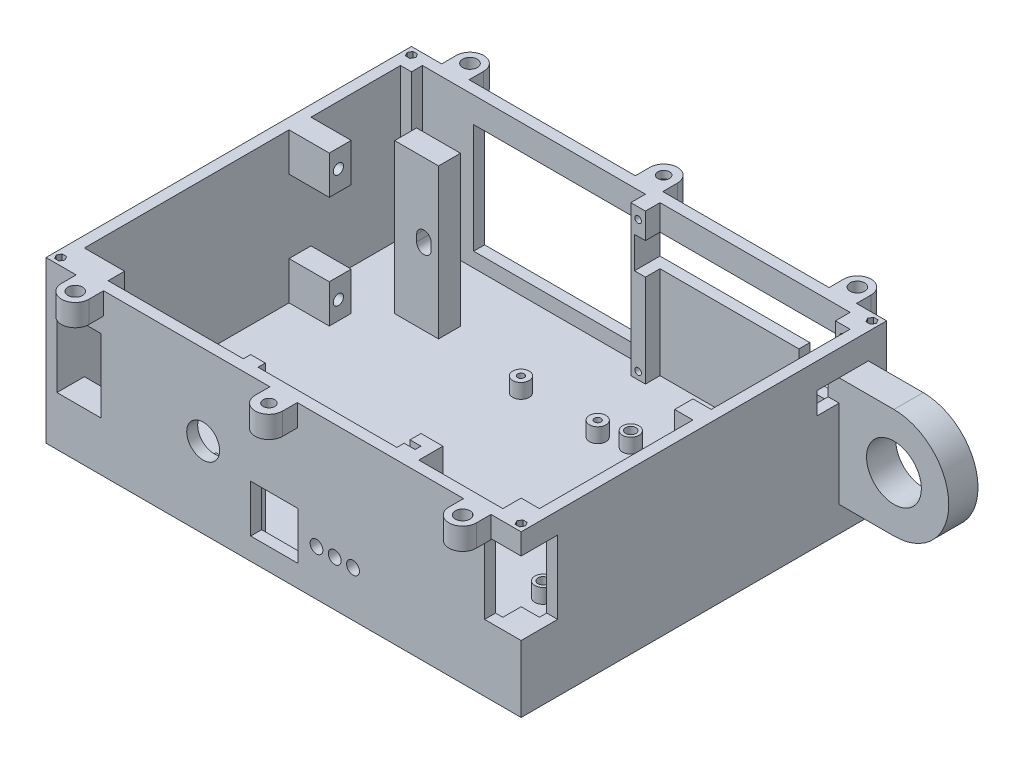
SolidWorks part; units mm, degrees
ref_plane "Front Plane" through (0, 0, 0) normal (0, 0, 1) x (1, 0, 0)
ref_plane "Top Plane" through (0, 0, 0) normal (0, 1, 0) x (1, 0, 0)
ref_plane "Right Plane" through (0, 0, 0) normal (1, 0, 0) x (0, 0, -1)
sketch "Sketch1" plane through (0, 0, 0) normal (0, 1, 0) x (1, 0, 0)
  line L1 (0, 0) -> (130, 0)
  line L2 (0, 0) -> (0, -100)
  line L3 (0, -100) -> (130, -100)
  line L4 (130, 0) -> (130, -100)
  dimension "D1" = 100
  dimension "D2" = 130
extrude "Boss-Extrude1" add sketch "Sketch1" along normal blind 44
sketch "Sketch3" plane through (0, 44, 0) normal (0, 1, 0) x (1, 0, 0)
  line L0 (0, 0) -> (0, -100) construction
  line L1 (14, -3) -> (67, -3)
  line L2 (3, -36.5) -> (3, -92.5)
  line L5 (127, -45) -> (127, -7)
  line L6 (122, -45) -> (127, -45)
  line L7 (130, 0) -> (0, 0) construction
  line L8 (3, -3) -> (14, -3) construction
  line L9 (14, -3) -> (14, -32) construction
  line L10 (14, -34) -> (14, -95) construction
  line L11 (14, -95) -> (14, -97) construction
  line L12 (14, -97) -> (122, -97)
  line L13 (14, -36.5) -> (3, -36.5)
  line L17 (14, -92.5) -> (3, -92.5)
  line L30 (127, -92) -> (127, -50)
  line L31 (130, -100) -> (130, 0) construction
  line L32 (0, -100) -> (130, -100) construction
  line L33 (122, -97) -> (122, -92.75) construction
  line L34 (122, -92.75) -> (122, -49.25) construction
  line L35 (122, -49.25) -> (122, -45) construction
  line L36 (122, -45) -> (122, -50)
  line L37 (122, -50) -> (127, -50)
  line L40 (122, -97) -> (122, -92)
  line L41 (122, -92) -> (127, -92)
  line L42 (14, -32) -> (14, -34) construction
  line L44 (14, -92.5) -> (14, -97)
  line L45 (127, -7) -> (125, -7) construction
  line L46 (125, -7) -> (69, -7) construction
  line L47 (69, -7) -> (67, -7) construction
  line L48 (71, -3) -> (123, -3)
  line L49 (67, -7) -> (71, -7)
  line L50 (67, -7) -> (67, -3)
  line L52 (71, -7) -> (71, -3)
  line L53 (127, -7) -> (123, -7)
  line L56 (123, -7) -> (123, -3)
  line L57 (14, -36.5) -> (14, -30.5)
  line L58 (14, -30.5) -> (3, -30.5)
  line L59 (3, -30.5) -> (3, -6)
  line L60 (14, -3) -> (6, -3)
  line L64 (3, -6) -> (6, -6)
  line L65 (6, -3) -> (6, -6)
  dimension "D1" = 3
  dimension "D2" = 3
  dimension "D3" = 3
  dimension "D4" = 3
  dimension "D5" = 65
  dimension "D6" = 61
  dimension "D7" = 2.5
  dimension "D8" = 2.5
  dimension "D9" = 43.5
  dimension "D10" = 5
  dimension "D11" = 6
  dimension "D12" = 5
  dimension "52" = 52
  dimension "D13" = 5
  dimension "D14" = 11
  dimension "D15" = 60
  dimension "D16" = 4
  dimension "D17" = 2
  dimension "D18" = 4
  dimension "D19" = 3
extrude "Cut-Extrude1" cut sketch "Sketch3" against normal blind 41
sketch "Sketch4" plane through (0, 0, 100) normal (0, 0, 1) x (1, 0, 0)
  line L0 (3, 44) -> (3, 33.5) construction
  line L1 (0, 44) -> (130, 44) construction
  line L2 (3, 33.5) -> (3, 13.5) construction
  line L3 (3, 13.5) -> (3, 3) construction
  line L5 (0, 44) -> (0, 0) construction
  line L6 (3, 3) -> (3, 0) construction
  line L7 (3, 33.5) -> (15, 33.5)
  line L8 (3, 33.5) -> (3, 13.5)
  line L9 (3, 13.5) -> (15, 13.5)
  line L10 (15, 33.5) -> (15, 13.5)
  line L11 (0, 0) -> (130, 0) construction
  dimension "D2" = 3
  dimension "D3" = 3
  dimension "D4" = 12
  dimension "D5" = 20
extrude "Cut-Extrude2" cut sketch "Sketch4" against normal up to surface (69.5 mm away) up to face at (8.5, 23.5, 30.5)
sketch "Sketch11" plane through (14, 0, 0) normal (1, 0, 0) x (0, 0, -1)
  line L0 (-95, 44) -> (-95, 39) construction
  line L1 (-100, 44) -> (0, 44) construction
  line L2 (-95, 39) -> (-95, 8) construction
  line L3 (-95, 8) -> (-95, 3) construction
  line L4 (-95, 3) -> (-95, 0) construction
  line L5 (-100, 0) -> (0, 0) construction
  line L6 (-100, 39) -> (-97, 39) construction
  line L7 (-100, 44) -> (-100, 0) construction
  line L8 (-97, 39) -> (-95, 39) construction
  line L9 (-95, 39) -> (-34, 39) construction
  line L10 (-34, 39) -> (-32, 39) construction
  line L11 (-32, 39) -> (0, 39) construction
  line L12 (0, 44) -> (0, 0) construction
  line L13 (-95, 8) -> (-34, 8) construction
  circle A0 centre (-95, 39) radius 1.4
  circle A1 centre (-95, 8) radius 1.4
  circle A2 centre (-34, 39) radius 1.4
  circle A3 centre (-34, 8) radius 1.4
  dimension "D6" = 2.8
  dimension "D1" = 3
  dimension "D2" = 31
  dimension "D3" = 3
  dimension "D4" = 65
  dimension "D5" = 61
extrude "Cut-Extrude6" cut sketch "Sketch11" against normal up to surface (11 mm away) up to face at (3, 23.5, 53.125)
sketch "Sketch12" plane through (0, 0, 0) normal (0, 0, -1) x (-1, 0, 0)
  line L0 (0, 37) -> (-3, 37) construction
  line L1 (0, 44) -> (0, 0) construction
  line L2 (-3, 37) -> (-17, 37) construction
  line L3 (-20, 37) -> (-66, 37) construction
  line L4 (-66, 37) -> (-66, 7) construction
  line L5 (-66, 37) -> (-66, 44) construction
  line L6 (-130, 44) -> (0, 44) construction
  line L7 (-66, 7) -> (-66, 0) construction
  line L8 (-130, 0) -> (0, 0) construction
  line L9 (-17, 37) -> (-20, 37) construction
  line L10 (-66, 37) -> (-20, 37)
  line L11 (-66, 37) -> (-66, 7)
  line L12 (-66, 7) -> (-20, 7)
  line L13 (-20, 37) -> (-20, 7)
  dimension "D1" = 3
  dimension "D2" = 3
  dimension "D3" = 46
  dimension "D4" = 30
  dimension "D5" = 14
extrude "Cut-Extrude7" cut sketch "Sketch12" against normal up to surface (3 mm away) up to face at (36.5, 23.5, 3)
sketch "Sketch14" plane through (0, 0, 97) normal (0, 0, -1) x (-1, 0, 0)
  line L0 (-66, 22) -> (-43, 22) construction
  line L1 (-66, 37) -> (-66, 7) construction
  line L2 (-43, 22) -> (-43, 7) construction
  line L3 (-66, 7) -> (-20, 7) construction
  circle A0 centre (-43, 22) radius 4.5
  dimension "D3" = 9
  dimension "D1" = 23
  dimension "D2" = 15
extrude "Cut-Extrude8" cut sketch "Sketch14" against normal up to surface (3 mm away) up to face at (9, 23.5, 100)
sketch "Sketch15" plane through (0, 0, 97) normal (0, 0, -1) x (-1, 0, 0)
  line L0 (-43, 22) -> (-43, 31.5) construction
  line L1 (-43, 22) -> (-43, 12.5) construction
  line L3 (-45.5, 29) -> (-40.5, 29)
  line L4 (-45.5, 29) -> (-45.5, 34)
  line L5 (-45.5, 34) -> (-40.5, 34)
  line L6 (-40.5, 29) -> (-40.5, 34)
  line L7 (-40.5, 15) -> (-45.5, 15)
  line L8 (-40.5, 15) -> (-40.5, 10)
  line L9 (-40.5, 10) -> (-45.5, 10)
  line L10 (-45.5, 15) -> (-45.5, 10)
  circle A0 centre (-43, 31.5) radius 1.4
  circle A1 centre (-43, 12.5) radius 1.4
  dimension "D7" = 2.8
  dimension "D1" = 9.5
  dimension "D2" = 2.5
  dimension "D3" = 2.5
  dimension "D4" = 5
  dimension "D5" = 2.5
  dimension "D6" = 2.5
extrude "Boss-Extrude2" add sketch "Sketch15" along normal blind 3
sketch "Sketch20" plane through (0, 44, 0) normal (0, 1, 0) x (1, 0, 0)
  line L0 (130, -97) -> (96, -97) construction
  line L1 (130, -100) -> (130, 0) construction
  line L2 (96, -97) -> (51, -97) construction
  line L3 (51, -97) -> (43, -97) construction
  line L4 (0, -100) -> (130, -100) construction
  line L5 (93, -97) -> (99, -97)
  line L6 (99, -97) -> (99, -90.4)
  line L7 (99, -90.4) -> (93, -90.4)
  line L8 (93, -90.4) -> (93, -93.4)
  line L9 (93, -93.4) -> (96, -93.4)
  line L10 (96, -93.4) -> (96, -95)
  line L11 (96, -95) -> (93, -95)
  line L12 (93, -95) -> (93, -97)
  line L14 (51, -97) -> (55, -97)
  line L15 (51, -97) -> (51, -95)
  line L16 (51, -95) -> (55, -95)
  line L17 (55, -97) -> (55, -95)
  dimension "D1" = 87
  dimension "D2" = 8
  dimension "D3" = 3
  dimension "40" = 45
  dimension "D5" = 3
  dimension "D6" = 3
  dimension "D7" = 1.6
  dimension "D8" = 2
  dimension "D9" = 3
  dimension "D10" = 3
  dimension "D11" = 2
  dimension "D12" = 4
extrude "Boss-Extrude3" add sketch "Sketch20" against normal up to surface (41 mm away) up to face at (66.5833, 3, 39.125)
sketch "Sketch21" plane through (130, 0, 0) normal (1, 0, 0) x (0, 0, -1)
  line L0 (0, 22) -> (-5, 22) construction
  line L1 (0, 44) -> (0, 0) construction
  line L2 (-5, 22) -> (-5, 37) construction
  line L4 (-5, 37) -> (-13, 37)
  line L5 (-5, 37) -> (-5, 7)
  line L6 (-5, 7) -> (-13, 7)
  line L7 (-13, 37) -> (-13, 7)
  dimension "D1" = 5
  dimension "D2" = 15
  dimension "D3" = 8
  dimension "D4" = 30
extrude "Boss-Extrude4" add sketch "Sketch21" along normal blind 30
sketch "Sketch23" plane through (0, 0, 5) normal (0, 0, -1) x (-1, 0, 0)
  line L0 (-160, 37) -> (-130, 7) construction
  line L2 (-145, 37) -> (-169.0246, 37)
  line L4 (-145, 7) -> (-169.0246, 7)
  line L5 (-169.0246, 37) -> (-169.0246, 7)
  circle A0 centre (-145, 22) radius 7.5
  arc A1 (-145, 37) -> (-145, 7) centre (-145, 22) ccw
  dimension "D1" = 15
  dimension "D2" = 15
extrude "Cut-Extrude9" cut sketch "Sketch23" against normal up to surface (8 mm away) up to face at (145, 22, 13)
sketch "Sketch24" plane through (130, 0, 0) normal (1, 0, 0) x (0, 0, -1)
  line L1 (-13, 37) -> (-19, 37)
  line L2 (-13, 37) -> (-13, 31)
  line L3 (-13, 31) -> (-19, 31)
  line L4 (-19, 37) -> (-19, 31)
  dimension "D1" = 6
extrude "Cut-Extrude10" cut sketch "Sketch24" against normal up to surface (3 mm away) up to face at (127, 23.5, 26)
sketch "Sketch25" plane through (0, 0, 95) normal (0, 0, -1) x (-1, 0, 0)
  line L0 (-53, 44) -> (-53, 41.65) construction
  line L1 (-130, 44) -> (0, 44) construction
  line L2 (-53, 41.65) -> (-53, 5.35) construction
  line L3 (-53, 5.35) -> (-53, 3) construction
  line L4 (-53, 3) -> (-53, 0) construction
  line L5 (-130, 0) -> (0, 0) construction
  line L6 (-55, 3) -> (-55, 44) construction
  circle A0 centre (-53, 41.65) radius 1
  circle A1 centre (-53, 5.35) radius 1
  dimension "D4" = 2
  dimension "D1" = 3
  dimension "D2" = 36.3
  dimension "D3" = 2
extrude "Cut-Extrude11" cut sketch "Sketch25" against normal blind 3
sketch "Sketch26" plane through (0, 3, 0) normal (0, 1, 0) x (1, 0, 0)
  line L0 (51, -97) -> (51, -80) construction
  line L1 (51, -15.6) -> (51, -26.05) construction
  line L2 (51, -15.6) -> (51, 0) construction
  line L3 (130, 0) -> (0, 0) construction
  line L4 (51, -26.05) -> (51, -69.55) construction
  line L5 (51, -69.55) -> (51, -80) construction
  line L6 (51, -26.05) -> (56, -26.05) construction
  line L8 (56, -26.05) -> (77, -26.05) construction
  line L9 (56, -26.05) -> (56, -69.55) construction
  line L10 (56, -69.55) -> (77, -69.55) construction
  line L11 (77, -26.05) -> (77, -69.55) construction
  circle A0 centre (56, -26.05) radius 2.25
  circle A1 centre (77, -26.05) radius 0.9
  circle A2 centre (56, -69.55) radius 2.25
  circle A3 centre (77, -69.55) radius 0.9
  circle A4 centre (56, -26.05) radius 0.9
  circle A5 centre (77, -26.05) radius 2.25
  circle A6 centre (56, -69.55) radius 0.9
  circle A7 centre (77, -69.55) radius 2.25
  dimension "D6" = 1.8
  dimension "D7" = 4.5
  dimension "D1" = 15.6
  dimension "D2" = 17
  dimension "D3" = 43.5
  dimension "D4" = 5
  dimension "D5" = 21
extrude "Boss-Extrude5" add sketch "Sketch26" along normal blind 4
sketch "Sketch27" plane through (122, 0, 0) normal (-1, 0, 0) x (0, 0, 1)
  line L0 (100, 40) -> (97, 40) construction
  line L1 (100, 44) -> (100, 0) construction
  line L2 (97, 40) -> (94.25, 40) construction
  line L3 (94.25, 40) -> (47.75, 40) construction
  line L4 (47.75, 40) -> (45, 40) construction
  line L5 (47.75, 40) -> (47.75, 16.5) construction
  line L6 (47.75, 16.5) -> (47.75, 3) construction
  line L7 (47.75, 3) -> (47.75, 0) construction
  line L8 (0, 0) -> (100, 0) construction
  line L9 (47.75, 40) -> (47.75, 44) construction
  line L10 (0, 44) -> (100, 44) construction
  line L11 (47.75, 16.5) -> (94.25, 16.5) construction
  circle A0 centre (47.75, 40) radius 0.9
  circle A1 centre (47.75, 16.5) radius 0.9
  circle A2 centre (94.25, 40) radius 0.9
  circle A3 centre (94.25, 16.5) radius 0.9
  dimension "D6" = 1.8
  dimension "D1" = 3
  dimension "D2" = 46.5
  dimension "D3" = 52
  dimension "D4" = 3
  dimension "D5" = 23.5
  dimension "D7" = 4
extrude "Cut-Extrude12" cut sketch "Sketch27" against normal up to surface (5 mm away) up to face at (127, 23.5, 71)
sketch "Sketch28" plane through (0, 0, 100) normal (0, 0, 1) x (1, 0, 0)
  line L0 (122, 0) -> (122, 3) construction
  line L1 (0, 0) -> (130, 0) construction
  line L2 (122, 38.25) -> (122, 40) construction
  line L3 (122, 18.25) -> (122, 38.25) construction
  line L4 (122, 40) -> (122, 44) construction
  line L7 (126, 38.25) -> (120, 38.25)
  line L8 (126, 38.25) -> (126, 18.25)
  line L9 (126, 18.25) -> (120, 18.25)
  line L10 (120, 38.25) -> (120, 18.25)
  line L11 (0, 44) -> (130, 44) construction
  line L12 (122, 18.25) -> (122, 16.5) construction
  line L13 (122, 16.5) -> (122, 3) construction
  dimension "D1" = 3
  dimension "D2" = 20
  dimension "D3" = 4
  dimension "D4" = 6
  dimension "D5" = 4
  dimension "D6" = 23.5
extrude "Cut-Extrude13" cut sketch "Sketch28" against normal up to surface (55 mm away) up to face at (124.5, 23.5, 45)
sketch "Sketch29" plane through (0, 0, 0) normal (0, 0, -1) x (-1, 0, 0)
  line L0 (-130, 37) -> (-123, 37) construction
  line L1 (-130, 44) -> (-130, 0) construction
  line L2 (-130, 44) -> (0, 44) construction
  line L3 (-123, 37) -> (-123, 20)
  line L4 (-123, 20) -> (-109, 20)
  line L5 (-109, 20) -> (-109, 28.3447)
  line L6 (-109, 28.3447) -> (-68, 28.3447)
  line L7 (-68, 28.3447) -> (-68, 37)
  line L8 (-68, 37) -> (-123, 37)
  dimension "D1" = 7
  dimension "D2" = 7
  dimension "D3" = 17
  dimension "D4" = 14
  dimension "D5" = 55
extrude "Cut-Extrude14" cut sketch "Sketch29" against normal up to surface (7 mm away) up to face at (69, 23.5, 7)
sketch "Sketch30" plane through (0, 0, 7) normal (0, 0, 1) x (1, 0, 0)
  line L0 (130, 41) -> (127, 41) construction
  line L1 (130, 44) -> (130, 0) construction
  line L2 (127, 41) -> (125, 41) construction
  line L3 (0, 44) -> (130, 44) construction
  line L5 (125, 41) -> (69, 41) construction
  line L6 (125, 41) -> (125, 5) construction
  line L7 (125, 5) -> (69, 5) construction
  line L8 (69, 41) -> (69, 5) construction
  circle A0 centre (69, 41) radius 0.9
  circle A1 centre (69, 5) radius 0.9
  circle A2 centre (125, 5) radius 0.9
  circle A3 centre (125, 41) radius 0.9
  dimension "D6" = 1.8
  dimension "D1" = 3
  dimension "D2" = 2
  dimension "D3" = 3
  dimension "D4" = 56
  dimension "D5" = 36
extrude "Cut-Extrude15" cut sketch "Sketch30" against normal up to surface (4 mm away) up to face at (101, 17.1149, 3)
sketch "Sketch31" plane through (0, 0, 97) normal (0, 0, -1) x (-1, 0, 0)
  line L0 (-55, 3) -> (-56, 3) construction
  line L1 (-55, 3) -> (-55, 44) construction
  line L2 (-56, 3) -> (-56, 6) construction
  line L3 (-130, 0) -> (0, 0) construction
  line L4 (-56, 6) -> (-69, 6)
  line L5 (-69, 6) -> (-69, 19)
  line L8 (-69, 19) -> (-56, 19)
  line L9 (-56, 19) -> (-56, 6)
  line L10 (-69, 12.5) -> (-74, 12.5) construction
  line L11 (-74, 12.5) -> (-79, 12.5) construction
  line L12 (-79, 12.5) -> (-84, 12.5) construction
  circle A0 centre (-74, 12.5) radius 1.75
  circle A1 centre (-79, 12.5) radius 1.75
  circle A2 centre (-84, 12.5) radius 1.75
  dimension "D7" = 3.5
  dimension "D1" = 3
  dimension "D2" = 1
  dimension "D3" = 3
  dimension "D4" = 13
  dimension "D5" = 13
  dimension "D6" = 5
extrude "Cut-Extrude16" cut sketch "Sketch31" against normal up to surface (3 mm away) up to face at (123, 28.25, 100)
sketch "Sketch34" plane through (0, 3, 0) normal (0, 1, 0) x (1, 0, 0)
  line L0 (3, -18.6) -> (20, -18.6) construction
  line L1 (3, -6) -> (3, -30.5) construction
  line L2 (67, -3) -> (6, -3) construction
  line L4 (20, -18.6) -> (32, -18.6)
  line L5 (20, -18.6) -> (20, -24.6)
  line L6 (20, -24.6) -> (32, -24.6)
  line L7 (32, -18.6) -> (32, -24.6)
  dimension "D1" = 17
  dimension "D2" = 15.6
  dimension "D3" = 12
  dimension "D4" = 6
extrude "Boss-Extrude6" add sketch "Sketch34" along normal up to surface (41 mm away) up to face at (71.4444, 44, 57.6278)
sketch "Sketch35" plane through (0, 0, 18.6) normal (0, 0, -1) x (-1, 0, 0)
  line L0 (-20, 23) -> (-28, 23) construction
  line L1 (-20, 7) -> (-20, 37) construction
  line L2 (-20, 37) -> (-66, 37) construction
  line L3 (-20, 24.8) -> (-28, 24.8) construction
  line L6 (-30, 24.8) -> (-30, 23)
  line L8 (-26, 24.8) -> (-26, 23)
  arc A0 (-30, 23) -> (-26, 23) centre (-28, 23) ccw
  arc A2 (-26, 24.8) -> (-30, 24.8) centre (-28, 24.8) ccw
  dimension "D3" = 4
  dimension "D1" = 8
  dimension "D2" = 14
  dimension "D4" = 12.2
extrude "Cut-Extrude17" cut sketch "Sketch35" against normal up to surface (6 mm away) up to face at (26, 23.5, 24.6)
sketch "Sketch36" plane through (0, 44, 0) normal (0, 1, 0) x (1, 0, 0)
  line L0 (0, 0) -> (12, 0) construction
  line L1 (65, 0) -> (12, 0) construction
  line L2 (130, 0) -> (0, 0) construction
  line L3 (65, 0) -> (118, 0) construction
  line L4 (118, 0) -> (130, 0) construction
  line L5 (0, 0) -> (0, -100) construction
  line L6 (0, -100) -> (130, -100) construction
  line L7 (65, 0) -> (65, -100) construction
  line L8 (118, 0) -> (118, -100) construction
  line L10 (12, 4) -> (118, 4) construction
  line L11 (118, 4) -> (118, 0) construction
  line L12 (65, 0) -> (65, 4) construction
  line L13 (12, -100) -> (12, -104) construction
  line L14 (12, -104) -> (118, -104) construction
  line L15 (118, -104) -> (118, -100) construction
  line L16 (65, -100) -> (65, -104) construction
  line L19 (8.25, 4) -> (8.25, 0)
  line L20 (8.25, 0) -> (15.75, 0)
  line L21 (15.75, 4) -> (15.75, 0)
  line L23 (61.25, 4) -> (61.25, 0)
  line L24 (61.25, 0) -> (68.75, 0)
  line L25 (68.75, 4) -> (68.75, 0)
  line L27 (114.25, 4) -> (114.25, 0)
  line L28 (114.25, 0) -> (121.75, 0)
  line L29 (121.75, 4) -> (121.75, 0)
  line L31 (8.25, -104) -> (8.25, -100)
  line L32 (8.25, -100) -> (15.75, -100)
  line L33 (15.75, -104) -> (15.75, -100)
  line L35 (61.25, -104) -> (61.25, -100)
  line L36 (61.25, -100) -> (68.75, -100)
  line L37 (68.75, -104) -> (68.75, -100)
  line L39 (121.75, -104) -> (121.75, -100)
  line L40 (121.75, -100) -> (114.25, -100)
  line L41 (114.25, -104) -> (114.25, -100)
  arc A0 (15.75, 4) -> (8.25, 4) centre (12, 4) ccw
  circle A1 centre (12, 4) radius 2
  arc A2 (68.75, 4) -> (61.25, 4) centre (65, 4) ccw
  circle A3 centre (65, 4) radius 1.6
  arc A4 (121.75, 4) -> (114.25, 4) centre (118, 4) ccw
  circle A5 centre (118, 4) radius 2
  arc A6 (8.25, -104) -> (15.75, -104) centre (12, -104) ccw
  circle A7 centre (12, -104) radius 2
  arc A8 (61.25, -104) -> (68.75, -104) centre (65, -104) ccw
  circle A9 centre (65, -104) radius 1.6
  arc A10 (114.25, -104) -> (121.75, -104) centre (118, -104) ccw
  circle A11 centre (118, -104) radius 2
  dimension "D1" = 4
  dimension "D2" = 7.5
  dimension "D4" = 3.2
  dimension "D3" = 4
  dimension "D5" = 12
  dimension "D6" = 4
extrude "Boss-Extrude7" add sketch "Sketch36" against normal blind 6
sketch "Sketch37" plane through (0, 38, 0) normal (0, -1, 0) x (1, 0, 0)
  circle A0 centre (65, 104) radius 2
  circle A1 centre (65, -4) radius 2
  dimension "D1" = 4
extrude "Cut-Extrude18" cut sketch "Sketch37" against normal blind 4 contours A1
sketch "Sketch38" plane through (0, 3, 0) normal (0, 1, 0) x (1, 0, 0)
  line L0 (84, -47.8) -> (77, -47.8) construction
  line L1 (84, -24) -> (107.6, -24) construction
  line L2 (84, -24) -> (84, -71.6) construction
  line L3 (84, -71.6) -> (107.6, -71.6) construction
  line L4 (107.6, -24) -> (107.6, -71.6) construction
  line L5 (77, -47.8) -> (77, -26.05) construction
  line L6 (77, -47.8) -> (77, -69.55) construction
  circle A0 centre (84, -24) radius 1.4
  circle A1 centre (84, -24) radius 2.25
  circle A2 centre (107.6, -24) radius 1.4
  circle A3 centre (107.6, -24) radius 2.25
  circle A4 centre (84, -71.6) radius 2.25
  circle A5 centre (84, -71.6) radius 1.4
  circle A6 centre (107.6, -71.6) radius 2.25
  circle A7 centre (107.6, -71.6) radius 1.4
  dimension "D3" = 2.8
  dimension "D4" = 4.5
  dimension "D1" = 47.6
  dimension "D2" = 23.6
  dimension "D5" = 7
extrude "Boss-Extrude8" add sketch "Sketch38" along normal blind 4
sketch "Sketch40" plane through (0, 0, 45) normal (0, 0, -1) x (-1, 0, 0)
  line L0 (-127, 44) -> (-127, 40) construction
  line L1 (-130, 44) -> (-121.75, 44) construction
  line L2 (-127, 40) -> (-127, 38.25) construction
  line L3 (-127, 38.25) -> (-127, 18.25) construction
  line L5 (-127, 18.25) -> (-127, 16.5) construction
  line L6 (-127, 16.5) -> (-127, 0) construction
  line L7 (-130, 0) -> (0, 0) construction
  line L8 (-130, 44) -> (-130, 0) construction
  line L10 (-127, 38.25) -> (-122, 38.25)
  line L11 (-127, 38.25) -> (-127, 18.25)
  line L12 (-127, 18.25) -> (-122, 18.25)
  line L13 (-122, 38.25) -> (-122, 18.25)
  dimension "D1" = 4
  dimension "D2" = 23.5
  dimension "D3" = 20
  dimension "D4" = 3
  dimension "D5" = 5
extrude "Cut-Extrude20" cut sketch "Sketch40" against normal up to surface (52 mm away) up to face at (115.75, 25.875, 97)
sketch "Sketch41" plane through (0, 0, 100) normal (0, 0, 1) x (1, 0, 0)
  line L0 (130, 31) -> (130, 7) construction
  line L1 (126, 38.25) -> (130, 38.25)
  line L2 (126, 38.25) -> (126, 18.25)
  line L3 (126, 18.25) -> (130, 18.25)
  line L4 (130, 38.25) -> (130, 18.25)
  dimension "D1" = 20
extrude "Cut-Extrude21" cut sketch "Sketch41" against normal blind 10
sketch "Sketch42" plane through (0, 44, 0) normal (0, 1, 0) x (1, 0, 0)
  line L0 (130, -100) -> (130, 0) construction
  line L1 (2, -2) -> (128, -2) construction
  line L2 (2, -2) -> (2, -98) construction
  line L3 (2, -98) -> (128, -98) construction
  line L4 (128, -2) -> (128, -98) construction
  line L5 (121.75, -100) -> (130, -100) construction
  line L6 (0, 0) -> (0, -100) construction
  line L7 (61.25, 0) -> (15.75, 0) construction
  line L9 (3.2124, -2) -> (2.6062, -0.95)
  line L10 (2.6062, -0.95) -> (1.3938, -0.95)
  line L11 (1.3938, -0.95) -> (0.7876, -2)
  line L12 (0.7876, -2) -> (1.3938, -3.05)
  line L13 (1.3938, -3.05) -> (2.6062, -3.05)
  line L14 (2.6062, -3.05) -> (3.2124, -2)
  line L15 (126.7876, -2) -> (127.3938, -3.05)
  line L16 (127.3938, -3.05) -> (128.6062, -3.05)
  line L17 (128.6062, -3.05) -> (129.2124, -2)
  line L18 (129.2124, -2) -> (128.6062, -0.95)
  line L19 (128.6062, -0.95) -> (127.3938, -0.95)
  line L20 (127.3938, -0.95) -> (126.7876, -2)
  line L21 (126.7876, -98) -> (127.3938, -99.05)
  line L22 (127.3938, -99.05) -> (128.6062, -99.05)
  line L23 (128.6062, -99.05) -> (129.2124, -98)
  line L24 (129.2124, -98) -> (128.6062, -96.95)
  line L25 (128.6062, -96.95) -> (127.3938, -96.95)
  line L26 (127.3938, -96.95) -> (126.7876, -98)
  line L27 (3.2124, -98) -> (2.6062, -96.95)
  line L28 (2.6062, -96.95) -> (1.3938, -96.95)
  line L29 (1.3938, -96.95) -> (0.7876, -98)
  line L30 (0.7876, -98) -> (1.3938, -99.05)
  line L31 (1.3938, -99.05) -> (2.6062, -99.05)
  line L32 (2.6062, -99.05) -> (3.2124, -98)
  circle A0 centre (2, -2) radius 1.05 construction
  circle A1 centre (128, -2) radius 1.05 construction
  circle A2 centre (128, -98) radius 1.05 construction
  circle A3 centre (2, -98) radius 1.05 construction
  dimension "D5" = 2.1
  dimension "D1" = 2
  dimension "D2" = 2
  dimension "D3" = 2
  dimension "D4" = 2
extrude "Cut-Extrude22" cut sketch "Sketch42" against normal blind 2.3
